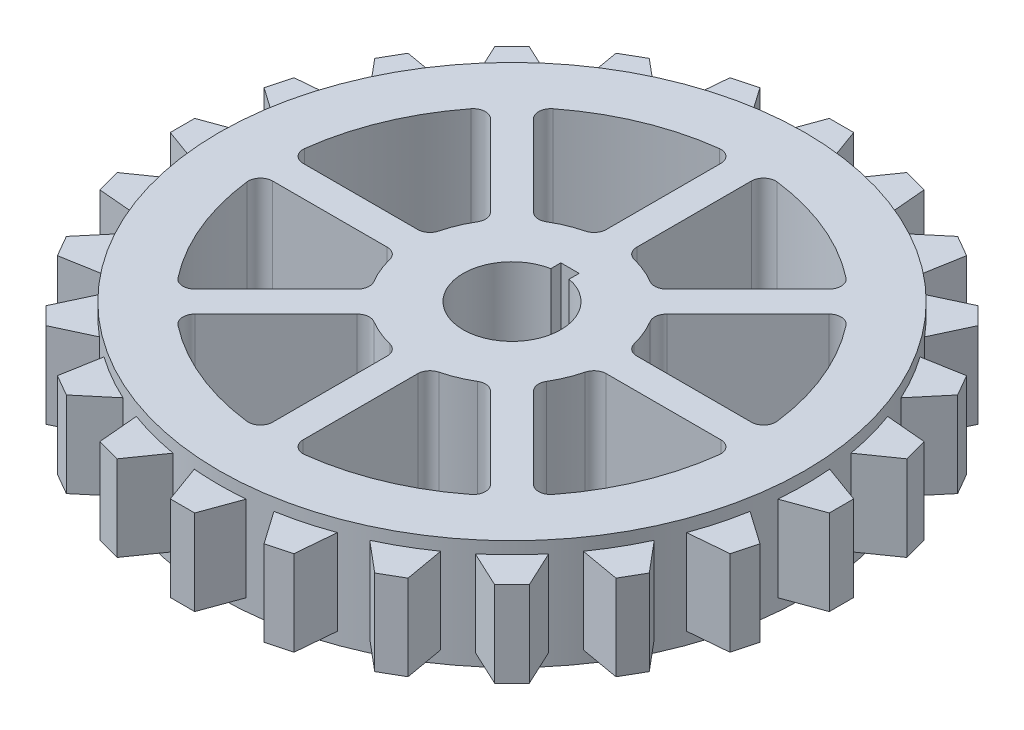
SolidWorks part; units mm, degrees
ref_plane "Front Plane" through (0, 0, 0) normal (0, 0, 1) x (1, 0, 0)
ref_plane "Top Plane" through (0, 0, 0) normal (0, 1, 0) x (1, 0, 0)
ref_plane "Right Plane" through (0, 0, 0) normal (1, 0, 0) x (0, 0, -1)
sketch "Sketch1" plane through (0, 0, 0) normal (0, 1, 0) x (1, 0, 0)
  line L27 (-1.5, 7.8581) -> (-1.5, 9.5066)
  line L28 (-1.5, 9.5066) -> (1.5, 9.5066)
  line L29 (1.5, 7.8581) -> (1.5, 9.5066)
  circle A0 centre (0, 0) radius 48
  circle A2 centre (0, 0) radius 14
  arc A3 (-1.5, 7.8581) -> (1.5, 7.8581) centre (0, 0) ccw
  circle A5 centre (0, 0) radius 41.5
  point P5 (0, 0)
  point P6 (0, 0)
  point P13 (0, 0)
  point P17 (0, 0)
  point P19 (0, 0)
  point P107 (0, 0)
  point P109 (0, 9.5066)
  dimension "D5" = 96
  dimension "D6" = 83
  dimension "D10" = 3
extrude "Boss-Extrude1" add sketch "Sketch1" along normal blind 18
ref_plane "Plane1" through (0, 17, 0) normal (0, 1, 0) x (1, 0, 0)
sketch "Sketch2" plane through (0, 17, 0) normal (0, 1, 0) x (1, 0, 0)
  line L0 (0, -9.9) -> (0, 9.9) construction
  line L2 (-2.5, 17.9444) -> (-2.5, 36.7253)
  line L4 (2.5, 17.9444) -> (2.5, 36.7253)
  line L6 (10.9208, 14.4563) -> (24.201, 27.7365)
  line L7 (14.4563, 10.9208) -> (27.7365, 24.201)
  line L8 (17.9444, 2.5) -> (36.7253, 2.5)
  line L9 (17.9444, -2.5) -> (36.7253, -2.5)
  line L10 (14.4563, -10.9208) -> (27.7365, -24.201)
  line L11 (10.9208, -14.4563) -> (24.201, -27.7365)
  line L12 (2.5, -17.9444) -> (2.5, -36.7253)
  line L13 (-2.5, -17.9444) -> (-2.5, -36.7253)
  line L14 (-10.9208, -14.4563) -> (-24.201, -27.7365)
  line L15 (-14.4563, -10.9208) -> (-27.7365, -24.201)
  line L16 (-17.9444, -2.5) -> (-36.7253, -2.5)
  line L17 (-17.9444, 2.5) -> (-36.7253, 2.5)
  line L18 (-14.4563, 10.9208) -> (-27.7365, 24.201)
  line L19 (-10.9208, 14.4563) -> (-24.201, 27.7365)
  arc A1 (-4.7432, 38.7105) -> (-24.0185, 30.7264) centre (0, 0) ccw
  circle A2 centre (0, 0) radius 14
  arc A3 (-4.0135, 16.0044) -> (-8.4789, 14.1548) centre (0, 0) ccw
  arc A4 (-2.5, 36.7253) -> (-4.7432, 38.7105) centre (-4.5, 36.7253) ccw
  arc A5 (2.5, 36.7253) -> (4.7432, 38.7105) centre (4.5, 36.7253) cw
  arc A6 (-4.0135, 16.0044) -> (-2.5, 17.9444) centre (-4.5, 17.9444) ccw
  arc A7 (4.0135, 16.0044) -> (2.5, 17.9444) centre (4.5, 17.9444) cw
  arc A8 (24.201, 27.7365) -> (24.0185, 30.7264) centre (22.7868, 29.1507) ccw
  arc A9 (27.7365, 24.201) -> (30.7264, 24.0185) centre (29.1507, 22.7868) cw
  arc A10 (14.1548, 8.4789) -> (14.4563, 10.9208) centre (15.8706, 9.5066) cw
  arc A11 (8.4789, 14.1548) -> (10.9208, 14.4563) centre (9.5066, 15.8706) ccw
  arc A12 (36.7253, 2.5) -> (38.7105, 4.7432) centre (36.7253, 4.5) ccw
  arc A13 (36.7253, -2.5) -> (38.7105, -4.7432) centre (36.7253, -4.5) cw
  arc A14 (16.0044, -4.0135) -> (17.9444, -2.5) centre (17.9444, -4.5) cw
  arc A15 (16.0044, 4.0135) -> (17.9444, 2.5) centre (17.9444, 4.5) ccw
  arc A16 (27.7365, -24.201) -> (30.7264, -24.0185) centre (29.1507, -22.7868) ccw
  arc A17 (24.201, -27.7365) -> (24.0185, -30.7264) centre (22.7868, -29.1507) cw
  arc A18 (8.4789, -14.1548) -> (10.9208, -14.4563) centre (9.5066, -15.8706) cw
  arc A19 (14.1548, -8.4789) -> (14.4563, -10.9208) centre (15.8706, -9.5066) ccw
  arc A20 (2.5, -36.7253) -> (4.7432, -38.7105) centre (4.5, -36.7253) ccw
  arc A21 (-2.5, -36.7253) -> (-4.7432, -38.7105) centre (-4.5, -36.7253) cw
  arc A22 (-4.0135, -16.0044) -> (-2.5, -17.9444) centre (-4.5, -17.9444) cw
  arc A23 (4.0135, -16.0044) -> (2.5, -17.9444) centre (4.5, -17.9444) ccw
  arc A24 (-24.201, -27.7365) -> (-24.0185, -30.7264) centre (-22.7868, -29.1507) ccw
  arc A25 (-27.7365, -24.201) -> (-30.7264, -24.0185) centre (-29.1507, -22.7868) cw
  arc A26 (-14.1548, -8.4789) -> (-14.4563, -10.9208) centre (-15.8706, -9.5066) cw
  arc A27 (-8.4789, -14.1548) -> (-10.9208, -14.4563) centre (-9.5066, -15.8706) ccw
  arc A28 (-36.7253, -2.5) -> (-38.7105, -4.7432) centre (-36.7253, -4.5) ccw
  arc A29 (-36.7253, 2.5) -> (-38.7105, 4.7432) centre (-36.7253, 4.5) cw
  arc A30 (-16.0044, 4.0135) -> (-17.9444, 2.5) centre (-17.9444, 4.5) cw
  arc A31 (-16.0044, -4.0135) -> (-17.9444, -2.5) centre (-17.9444, -4.5) ccw
  arc A32 (-27.7365, 24.201) -> (-30.7264, 24.0185) centre (-29.1507, 22.7868) ccw
  arc A33 (-24.201, 27.7365) -> (-24.0185, 30.7264) centre (-22.7868, 29.1507) cw
  arc A34 (-8.4789, 14.1548) -> (-10.9208, 14.4563) centre (-9.5066, 15.8706) cw
  arc A35 (-14.1548, 8.4789) -> (-14.4563, 10.9208) centre (-15.8706, 9.5066) ccw
  arc A36 (-30.7264, 24.0185) -> (-38.7105, 4.7432) centre (0, 0) ccw
  arc A37 (-14.1548, 8.4789) -> (-16.0044, 4.0135) centre (0, 0) ccw
  arc A38 (24.0185, 30.7264) -> (4.7432, 38.7105) centre (0, 0) ccw
  arc A39 (8.4789, 14.1548) -> (4.0135, 16.0044) centre (0, 0) ccw
  arc A40 (38.7105, 4.7432) -> (30.7264, 24.0185) centre (0, 0) ccw
  arc A41 (16.0044, 4.0135) -> (14.1548, 8.4789) centre (0, 0) ccw
  arc A42 (30.7264, -24.0185) -> (38.7105, -4.7432) centre (0, 0) ccw
  arc A43 (14.1548, -8.4789) -> (16.0044, -4.0135) centre (0, 0) ccw
  arc A44 (4.7432, -38.7105) -> (24.0185, -30.7264) centre (0, 0) ccw
  arc A45 (4.0135, -16.0044) -> (8.4789, -14.1548) centre (0, 0) ccw
  arc A46 (-24.0185, -30.7264) -> (-4.7432, -38.7105) centre (0, 0) ccw
  arc A47 (-8.4789, -14.1548) -> (-4.0135, -16.0044) centre (0, 0) ccw
  arc A48 (-16.0044, -4.0135) -> (-14.1548, -8.4789) centre (0, 0) ccw
  arc A49 (-38.7105, -4.7432) -> (-30.7264, -24.0185) centre (0, 0) ccw
  point P106 (0, 0)
  dimension "D2" = 78
  dimension "D3" = 28
  dimension "D4" = 33
  dimension "D6" = 4
  dimension "D7" = 4
  dimension "D5" = 8
extrude "Cut-Extrude1" cut sketch "Sketch2" against normal through all both and the other way through all contours A28 A49 A25 L15 A26 A48 A31 L16 | A47 A27 L14 A24 A46 A21 L13 A22 | A45 A23 L12 A20 A44 A17 L11 A18 | A41 A15 L8 A12 A40 A9 L7 A10 | A39 A11 L6 A8 A38 A5 L4 A7 | A34 A3 A6 L2 A4 A1 A33 L19 | A37 A35 L18 A32 A36 A29 L17 A30 | L9 A13 A42 A16 L10 A19 A43 A14
sketch "Sketch5" plane through (0, 0, 0) normal (0, -1, 0) x (1, 0, 0)
  circle A0 centre (0, 0) radius 41.5
  dimension "D1" = 83
extrude "Cut-Extrude2" cut sketch "Sketch5" against normal blind 1
ref_plane "Plane2" through (0, 2, 0) normal (0, -1, 0) x (-1, 0, 0)
sketch "Sketch8" plane through (0, 2, 0) normal (0, -1, 0) x (-1, 0, 0)
  line L1 (-2, 54) -> (2, 54)
  line L2 (2, 54) -> (4.2525, 47.8113)
  line L3 (-2, 54) -> (-4.2525, 47.8113)
  arc A1 (4.2525, 47.8113) -> (-4.2525, 47.8113) centre (0, 0) ccw
  point P8 (0, 54)
  dimension "D2" = 4
  dimension "D3" = 40
extrude "Boss-Extrude2" add sketch "Sketch8" against normal blind 14
pattern_circular "CirPattern1" count 24 over 360 about axis through (0, 0, 0) along (0, 1, 0) of "Boss-Extrude2"
